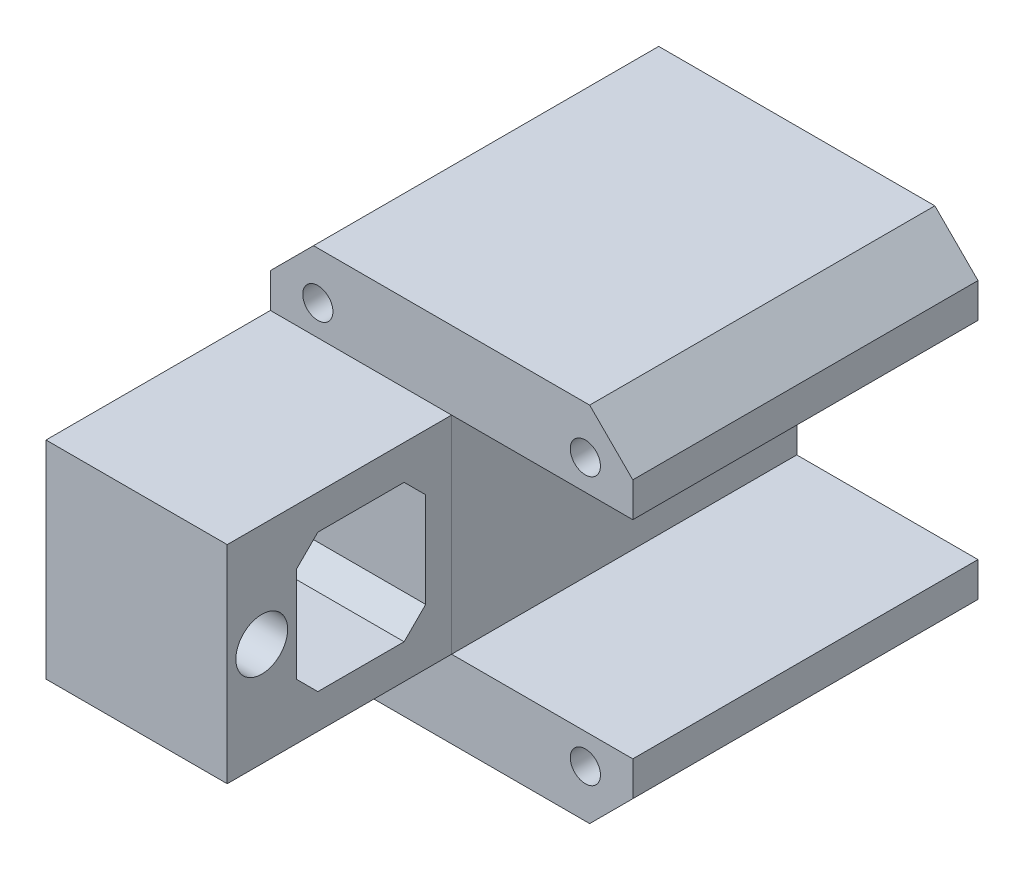
SolidWorks part; units mm, degrees
ref_plane "前基準面" through (0, 0, 0) normal (0, 0, 1) x (1, 0, 0)
ref_plane "上基準面" through (0, 0, 0) normal (0, 1, 0) x (1, 0, 0)
ref_plane "右基準面" through (0, 0, 0) normal (1, 0, 0) x (0, 0, -1)
sketch "草圖1" plane through (0, 0, 0) normal (0, 0, 1) x (1, 0, 0)
  line L1 (-21, 21) -> (21, 21)
  line L2 (-21, 21) -> (-21, -21)
  line L3 (-21, -21) -> (21, -21)
  line L4 (21, 21) -> (21, -21)
  point P4 (0, 21)
  point P6 (-21, 0)
  dimension "D1" = 42
  dimension "D2" = 42
extrude "填料-伸長1" add sketch "草圖1" along normal blind 40
chamfer "導角1" distance 5 angle 45 4 edges at (-21, -21, 20) (21, -21, 20) (21, 21, 20) (-21, 21, 20)
sketch "草圖4" plane through (0, 0, 40) normal (0, 0, 1) x (1, 0, 0)
  line L0 (-21, 16) -> (-21, -16) construction
  line L1 (16, 21) -> (-16, 21) construction
  line L2 (0, 21) -> (0, -21) construction
  line L3 (-16, -21) -> (16, -21) construction
  line L4 (0, -21) -> (21, 0) construction
  line L5 (21, -16) -> (21, 16) construction
  line L6 (21, 0) -> (-21, 0) construction
  circle A0 centre (-15.5, 15.5) radius 1.75
  circle A1 centre (-15.5, -15.5) radius 1.75
  circle A2 centre (15.5, -15.5) radius 1.75
  circle A3 centre (15.5, 15.5) radius 1.75
  dimension "D1" = 3.5
  dimension "D2" = 5.5
  dimension "D3" = 5.5
  dimension "D4" = 31
extrude "除料-伸長1" cut sketch "草圖4" against normal blind 3
sketch "草圖5" plane through (-21, 0, 0) normal (-1, 0, 0) x (0, 0, 1)
  line L0 (40, 16) -> (40, -16) construction
  line L1 (40, 12) -> (66, 12)
  line L2 (40, 12) -> (40, -12)
  line L3 (40, -12) -> (66, -12)
  line L4 (66, 12) -> (66, -12)
  line L5 (0, 0) -> (66, 0) construction
  line L7 (43, 8) -> (58, 8)
  line L8 (43, 8) -> (43, -8)
  line L9 (43, -8) -> (58, -8)
  line L10 (58, 8) -> (58, -8)
  dimension "D1" = 24
  dimension "D2" = 26
  dimension "D3" = 4
  dimension "D4" = 8
  dimension "D5" = 3
  dimension "D6" = 4
extrude "填料-伸長2" add sketch "草圖5" against normal blind 21 separate body
sketch "草圖7" plane through (21, 0, 0) normal (1, 0, 0) x (0, 0, -1)
  line L0 (0, -16) -> (0, 16) construction
  line L1 (-40, 12) -> (0, 12)
  line L2 (-40, 12) -> (-40, -12)
  line L3 (-40, -12) -> (0, -12)
  line L4 (0, 12) -> (0, -12)
  point P7 (0, 0)
extrude "除料-伸長3" cut sketch "草圖7" against normal blind 21
sketch "草圖6" plane through (0, 0, 0) normal (1, 0, 0) x (0, 0, -1)
  line L3 (-58, 8) -> (-66, 8) construction
  line L4 (-66, -12) -> (-66, 12) construction
  line L5 (-58, -8) -> (-66, -8) construction
  line L6 (-62, 8) -> (-62, -8) construction
  line L7 (-60.25, 0) -> (-20.25, 0) construction
  circle A0 centre (-62, 0) radius 3
  circle A1 centre (-62, 0) radius 1.75 construction
  circle A2 centre (-18.5, 0) radius 1.75 construction
  circle A3 centre (-18.5, 0) radius 3
  dimension "D1" = 6
  dimension "D4" = 3.5
  dimension "D3" = 3.5
  dimension "D5" = 6
  dimension "D2" = 40
extrude "除料-伸長2" cut sketch "草圖6" against normal blind 10
chamfer "導角2" distance 2.5 angle 45 4 edges at (-10.5, -8, 43) (-10.5, 8, 43) (-10.5, -8, 58) (-10.5, 8, 58)
